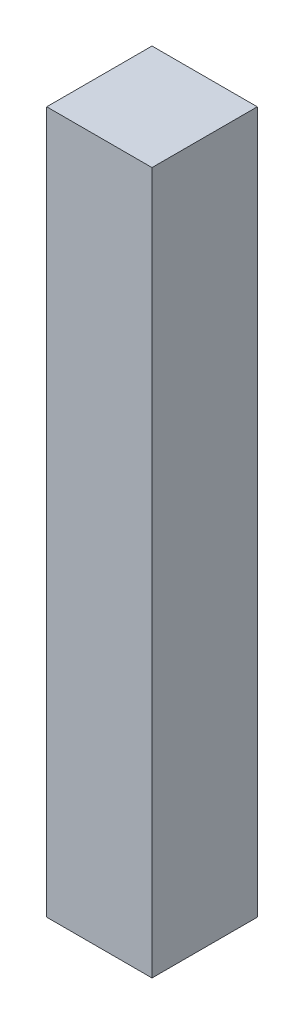
SolidWorks part; units mm, degrees
ref_plane "Front Plane" through (0, 0, 0) normal (0, 0, 1) x (1, 0, 0)
ref_plane "Top Plane" through (0, 0, 0) normal (0, 1, 0) x (1, 0, 0)
ref_plane "Right Plane" through (0, 0, 0) normal (1, 0, 0) x (0, 0, -1)
sketch "Sketch1" plane through (0, 0, 0) normal (0, 1, 0) x (1, 0, 0)
  line L1 (-7.5, 7.5) -> (7.5, 7.5)
  line L2 (-7.5, 7.5) -> (-7.5, -7.5)
  line L3 (-7.5, -7.5) -> (7.5, -7.5)
  line L4 (7.5, 7.5) -> (7.5, -7.5)
  line L5 (-7.5, 7.5) -> (7.5, -7.5) construction
  line L6 (-7.5, -7.5) -> (7.5, 7.5) construction
  point P0 (0, 0)
  point P6 (0, 0)
  dimension "D1" = 15
  dimension "D2" = 15
extrude "Boss-Extrude1" add sketch "Sketch1" along normal blind 100
